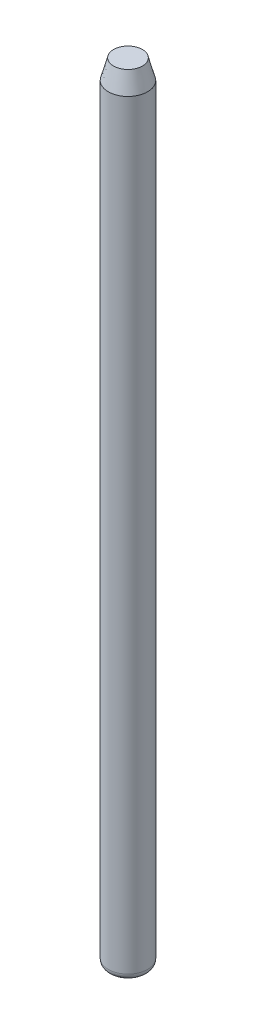
SolidWorks part; units mm, degrees
ref_plane "Front Plane" through (0, 0, 0) normal (0, 0, 1) x (1, 0, 0)
ref_plane "Top Plane" through (0, 0, 0) normal (0, 1, 0) x (1, 0, 0)
ref_plane "Right Plane" through (0, 0, 0) normal (1, 0, 0) x (0, 0, -1)
sketch "Sketch1" plane through (0, 0, 0) normal (0, 1, 0) x (1, 0, 0)
  circle A0 centre (0, 0) radius 1.5
  dimension "D1" = 3
extrude "Boss-Extrude1" add sketch "Sketch1" along normal blind 60
chamfer "Chamfer1" distance 1.5 angle 15 1 edges at (0, 60, 1.5)
fillet "Fillet1" radius 0.5 1 edges at (0, 0, 1.5)
